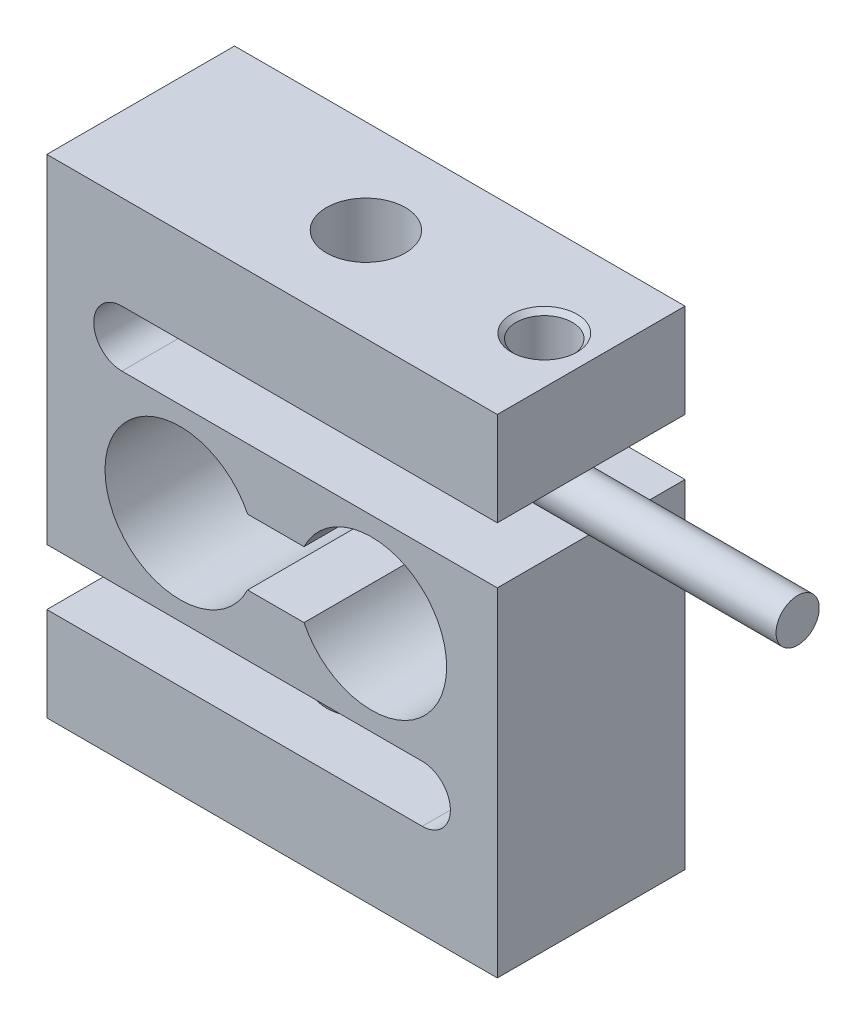
SolidWorks part; units mm, degrees
ref_plane "Front Plane" through (0, 0, 0) normal (0, 0, 1) x (1, 0, 0)
ref_plane "Top Plane" through (0, 0, 0) normal (0, 1, 0) x (1, 0, 0)
ref_plane "Right Plane" through (0, 0, 0) normal (1, 0, 0) x (0, 0, -1)
ref_plane "Ebene1" through (0, 0, 5) normal (0, 0, 1) x (1, 0, 0)
sketch "Skizze1" plane through (0, 0, 5) normal (0, 0, 1) x (1, 0, 0)
  line L0 (-12, 13) -> (-12, -13)
  line L1 (-12, -13) -> (12, -13)
  line L2 (12, -13) -> (12, 13)
  line L3 (12, 13) -> (-12, 13)
extrude "Aufsatz-Linear austragen1" add sketch "Skizze1" against normal blind 10
sketch "Skizze2" plane through (0, 0, -5) normal (0, 0, -1) x (-1, 0, 0)
  line L0 (12, -8) -> (12, -5)
  line L1 (12, -5) -> (-8, -5)
  line L2 (-8, -8) -> (12, -8)
  arc A0 (-8, -5) -> (-8, -8) centre (-8, -6.5) ccw
extrude "Schnitt-Linear austragen1" cut sketch "Skizze2" against normal through all
sketch "Skizze3" plane through (0, 0, -5) normal (0, 0, -1) x (-1, 0, 0)
  line L0 (-12, 8) -> (-12, 5)
  line L1 (-12, 5) -> (8, 5)
  line L2 (8, 8) -> (-12, 8)
  arc A0 (8, 5) -> (8, 8) centre (8, 6.5) ccw
extrude "Schnitt-Linear austragen2" cut sketch "Skizze3" against normal through all
sketch "Skizze4" plane through (0, 0, -5) normal (0, 0, -1) x (-1, 0, 0)
  line L0 (-1.7031, -1.75) -> (1.3031, -1.75)
  line L1 (1.3031, 1.75) -> (-1.7031, 1.75)
  arc A0 (-1.7031, 1.75) -> (-1.7031, -1.75) centre (-5.3, 0) cw
  arc A1 (1.3031, -1.75) -> (1.3031, 1.75) centre (4.9, 0) cw
extrude "Schnitt-Linear austragen3" cut sketch "Skizze4" against normal through all
sketch "Skizze5" plane through (0, 0, 0) normal (0, 1, 0) x (1, 0, 0)
  line L0 (9.3, 5) -> (5.3, 5)
  line L1 (5.3, 5) -> (5.3, -5)
  line L2 (5.3, -5) -> (9.3, -5)
  line L3 (9.3, -5) -> (9.3, 5)
  line L4 (5.3, 5) -> (5.3, -5) construction
revolve "Schnitt-Rotation1" cut sketch "Skizze5" angle 360 about L4
sketch "Skizze6" plane through (0, 0, 0) normal (0, 1, 0) x (1, 0, 0)
  line L0 (-0.9, 5) -> (-4.9, 5)
  line L1 (-4.9, 5) -> (-4.9, -5)
  line L2 (-4.9, -5) -> (-0.9, -5)
  line L3 (-0.9, -5) -> (-0.9, 5)
  line L4 (-4.9, 5) -> (-4.9, -5) construction
revolve "Schnitt-Rotation2" cut sketch "Skizze6" angle 360 about L4
hole_wizard "Ø2.3 (2.3) Durchmesser Bohrung1" positions "Skizze8" profile "Skizze7" hole size "Ø2.3" standard "ANSI Metrisch"
sketch "Skizze8" plane through (-12, 0, 0) normal (-1, 0, 0) x (0, 0, 1)
  point P0 (0, 6.5)
sketch "Skizze7" plane through (-12, 6.5, 0) normal (0, 1, 0) x (0, 0, 1)
  line L0 (0, 0) -> (0, 24)
  line L1 (0, 24) -> (1.15, 24)
  line L2 (1.15, 24) -> (1.15, 0)
  line L5 (1.15, 0) -> (0, 0)
  line L11 (0, -6.35) -> (0, 107.95) construction
  dimension "Bohrerdurchmesser" = 2.3
  dimension "Bohrungstiefe" = 24
hole_wizard "M5 Gewindebohrung1" positions "Skizze10" profile "Skizze9" tap size "M5" standard "DIN"
sketch "Skizze10" plane through (0, 8, 0) normal (0, -1, 0) x (-1, 0, 0)
  point P0 (0, 0)
sketch "Skizze9" plane through (0, 8, 0) normal (1, 0, 0) x (0, 0, -1)
  line L0 (0, 0) -> (0, 5)
  line L1 (0, 5) -> (2.1, 5)
  line L2 (2.1, 5) -> (2.1, 0)
  line L5 (2.1, 0) -> (0, 0)
  line L11 (0, -6.35) -> (0, 107.95) construction
  dimension "Bohrerdurchmesser" = 4.2
  dimension "Bohrungstiefe" = 5
cosmetic thread "Bohrungsgewinde1" parameters "D2"=5
hole_wizard "Ø3.0 (3) Durchmesser Bohrung1" positions "Skizze12" profile "Skizze11" hole size "Ø3.0" standard "ANSI Metrisch"
sketch "Skizze12" plane through (0, 13, 0) normal (0, 1, 0) x (1, 0, 0)
  point P0 (9.5, 0)
sketch "Skizze11" plane through (9.5, 13, 0) normal (1, 0, 0) x (0, 0, 1)
  line L0 (0, 0) -> (0, 5)
  line L1 (0, 5) -> (1.5, 5)
  line L2 (1.5, 5) -> (1.5, 0)
  line L5 (1.5, 0) -> (0, 0)
  line L11 (0, -6.35) -> (0, 107.95) construction
  dimension "Bohrerdurchmesser" = 3
  dimension "Bohrungstiefe" = 5
hole_wizard "M5 Gewindebohrung2" positions "Skizze14" profile "Skizze13" tap size "M5" standard "DIN"
sketch "Skizze14" plane through (0, -8, 0) normal (0, 1, 0) x (1, 0, 0)
  point P0 (0, 0)
sketch "Skizze13" plane through (0, -8, 0) normal (1, 0, 0) x (0, 0, 1)
  line L0 (0, 0) -> (0, 5)
  line L1 (0, 5) -> (2.1, 5)
  line L2 (2.1, 5) -> (2.1, 0)
  line L5 (2.1, 0) -> (0, 0)
  line L11 (0, -6.35) -> (0, 107.95) construction
  dimension "Bohrerdurchmesser" = 4.2
  dimension "Bohrungstiefe" = 5
cosmetic thread "Bohrungsgewinde2" parameters "D2"=5
hole_wizard "Ø3.0 (3) Durchmesser Bohrung2" positions "Skizze16" profile "Skizze15" hole size "Ø3.0" standard "ANSI Metrisch"
sketch "Skizze16" plane through (0, -13, 0) normal (0, -1, 0) x (-1, 0, 0)
  point P0 (9.5, 0)
sketch "Skizze15" plane through (-9.5, -13, 0) normal (1, 0, 0) x (0, 0, -1)
  line L0 (0, 0) -> (0, 5)
  line L1 (0, 5) -> (1.5, 5)
  line L2 (1.5, 5) -> (1.5, 0)
  line L5 (1.5, 0) -> (0, 0)
  line L11 (0, -6.35) -> (0, 107.95) construction
  dimension "Bohrerdurchmesser" = 3
  dimension "Bohrungstiefe" = 5
chamfer "Fase1" distance 0.25 angle 45 2 edges at (9.5, 13, 1.5) (-9.5, -13, -1.5)
sketch "Skizze24" plane through (-12, 0, 0) normal (-1, 0, 0) x (0, 0, 1)
  circle A0 centre (0, 6.5) radius 1.15
extrude "Sensorkabel" add sketch "Skizze24" against normal blind 35
